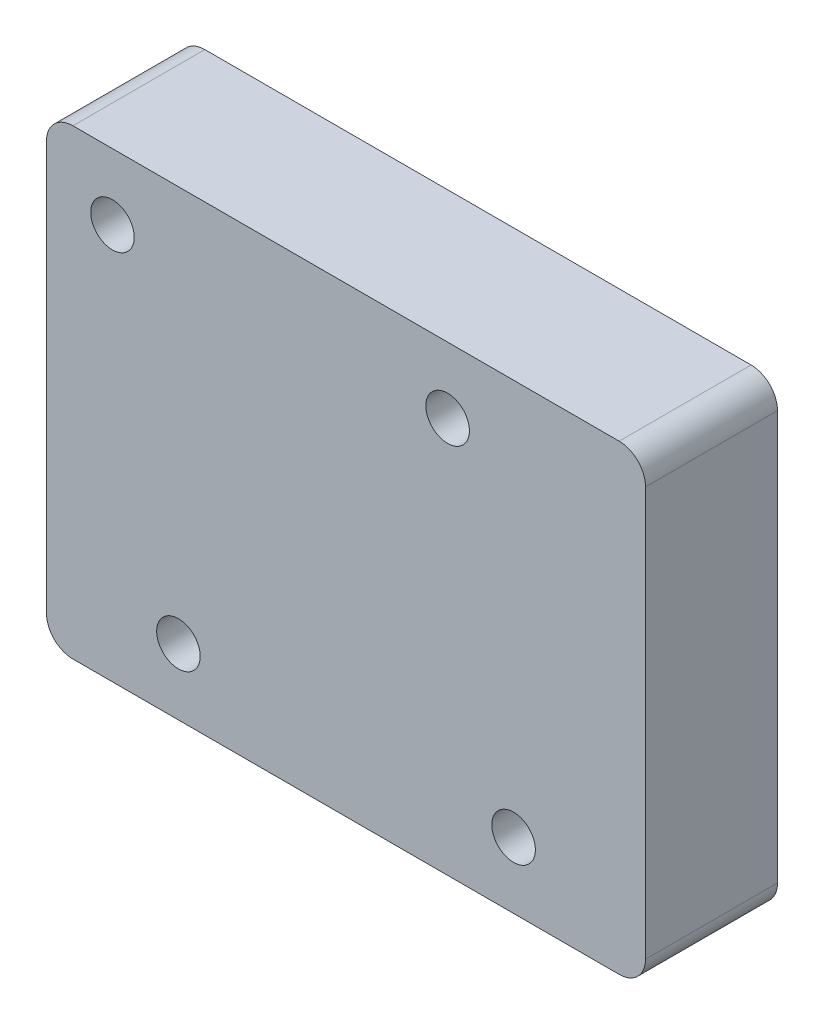
SolidWorks part; units mm, degrees
material "5052-H34"
ref_plane "正面" through (0, 0, 0) normal (0, 0, 1) x (1, 0, 0)
ref_plane "平面" through (0, 0, 0) normal (0, 1, 0) x (1, 0, 0)
ref_plane "右側面" through (0, 0, 0) normal (1, 0, 0) x (0, 0, -1)
sketch "ｽｹｯﾁ1" plane through (0, 0, 0) normal (0, 0, 1) x (1, 0, 0)
  line L1 (0, 0) -> (45.4, 0)
  line L2 (0, 0) -> (0, 35)
  line L3 (0, 35) -> (45.4, 35)
  line L4 (45.4, 0) -> (45.4, 35)
  circle A0 centre (10, 5) radius 1.65
  circle A1 centre (35.4, 5) radius 1.65
  circle A2 centre (5, 30) radius 1.65
  circle A3 centre (30.4, 30) radius 1.65
  dimension "D3" = 5
  dimension "D4" = 3.3
  dimension "D5" = 10
  dimension "D6" = 25.4
  dimension "D8" = 5
  dimension "D9" = 5
  dimension "D10" = 5
  dimension "D7" = 25.4
  dimension "D1" = 35
  dimension "D2" = 45.4
extrude "ﾎﾞｽ - 押し出し1" add sketch "ｽｹｯﾁ1" along normal blind 10
fillet "ﾌｨﾚｯﾄ1" radius 2 4 edges at (45.4, 0, 5) (45.4, 35, 5) (0, 0, 5) (0, 35, 5)
sketch "ｽｹｯﾁ2" plane through (0, 0, 0) normal (0, -1, 0) x (1, 0, 0)
  line L0 (0, 5) -> (45.4, 5) construction
  line L1 (0, 0) -> (0, 10) construction
  line L2 (45.4, 10) -> (45.4, 0) construction
  circle A0 centre (2.7, 5) radius 1.65
  circle A1 centre (42.7, 5) radius 1.65
  point P10 (22.7, 5)
  dimension "D1" = 3.3
  dimension "D2" = 40
  dimension "D3" = 20
extrude "ｶｯﾄ - 押し出し1" cut sketch "ｽｹｯﾁ2" against normal blind 10
